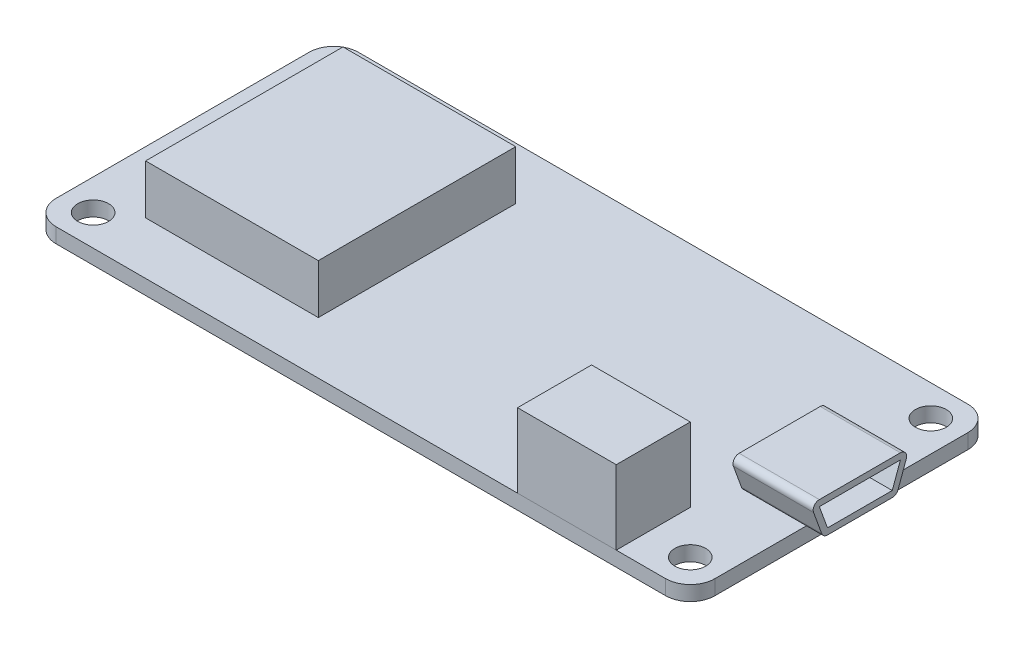
SolidWorks part; units mm, degrees
ref_plane "Front Plane" through (0, 0, 0) normal (0, 0, 1) x (1, 0, 0)
ref_plane "Top Plane" through (0, 0, 0) normal (0, 1, 0) x (1, 0, 0)
ref_plane "Right Plane" through (0, 0, 0) normal (1, 0, 0) x (0, 0, -1)
sketch "Sketch1" plane through (0, 0, 0) normal (0, 1, 0) x (1, 0, 0)
  line L1 (2, 0) -> (51.4, 0)
  line L2 (0, 2) -> (0, 22.5)
  line L3 (2, 24.5) -> (51.4, 24.5)
  line L4 (53.4, 2) -> (53.4, 22.5)
  line L5 (2.5, 22) -> (50.9, 22) construction
  line L6 (2.5, 22) -> (2.5, 2.5) construction
  line L7 (2.5, 2.5) -> (50.9, 2.5) construction
  line L8 (50.9, 22) -> (50.9, 2.5) construction
  arc A0 (51.4, 24.5) -> (53.4, 22.5) centre (51.4, 22.5) cw
  arc A1 (51.4, 0) -> (53.4, 2) centre (51.4, 2) ccw
  arc A2 (2, 0) -> (0, 2) centre (2, 2) cw
  arc A3 (0, 22.5) -> (2, 24.5) centre (2, 22.5) cw
  circle A4 centre (2.5, 22) radius 1.25
  circle A5 centre (50.9, 22) radius 1.25
  circle A6 centre (50.9, 2.5) radius 1.25
  circle A7 centre (2.5, 2.5) radius 1.25
  point P7 (53.4, 24.5)
  point P12 (0, 0)
  point P15 (0, 24.5)
  dimension "D2" = 2
  dimension "D3" = 2.5
  dimension "D1" = 24.5
  dimension "48.5" = 53.4
  dimension "D4" = 2.5
  dimension "D5" = 2.5
  dimension "D6" = 2.5
  dimension "D7" = 2.5
extrude "Boss-Extrude1" add sketch "Sketch1" along normal blind 1.2
sketch "Sketch2" plane through (53.4, 0, 0) normal (1, 0, 0) x (0, 0, -1)
  line L0 (2, 1.2) -> (22.5, 1.2) construction
  line L1 (8.9641, 4.0191) -> (15.5359, 4.0191)
  line L2 (8.4942, 3.3481) -> (9.1563, 1.529)
  line L3 (9.6262, 1.2) -> (14.8738, 1.2)
  line L4 (16.0058, 3.3481) -> (15.3437, 1.529)
  line L5 (8.9641, 3.5191) -> (9.6262, 1.7)
  line L6 (9.6262, 1.7) -> (14.8738, 1.7)
  line L7 (15.5359, 3.5191) -> (14.8738, 1.7)
  line L8 (8.9641, 3.5191) -> (15.5359, 3.5191)
  arc A0 (9.1563, 1.529) -> (9.6262, 1.2) centre (9.6262, 1.7) ccw
  arc A1 (14.8738, 1.2) -> (15.3437, 1.529) centre (14.8738, 1.7) ccw
  arc A2 (15.5359, 4.0191) -> (16.0058, 3.3481) centre (15.5359, 3.5191) cw
  arc A3 (8.9641, 4.0191) -> (8.4942, 3.3481) centre (8.9641, 3.5191) ccw
  arc A4 (8.9641, 3.5191) -> (8.9641, 3.5191) centre (8.9641, 3.5191) ccw
  arc A5 (9.6262, 1.7) -> (9.6262, 1.7) centre (9.6262, 1.7) ccw
  arc A6 (14.8738, 1.7) -> (14.8738, 1.7) centre (14.8738, 1.7) ccw
  arc A7 (15.5359, 3.5191) -> (15.5359, 3.5191) centre (15.5359, 3.5191) cw
  point P4 (12.25, 1.2)
  point P5 (12.25, 1.2)
  point P10 (9.2761, 1.2)
  point P15 (16.25, 4.0191)
  point P18 (8.25, 4.0191)
  dimension "D3" = 0.5
  dimension "D1" = 3
  dimension "D2" = 8
  dimension "D5" = 110
  dimension "D6" = 110
  dimension "D4" = 0.5
extrude "Boss-Extrude2" add sketch "Sketch2" against normal blind 5 and the other way blind 1.5 separate body
sketch "Sketch3" plane through (0, 1.2, 0) normal (0, 1, 0) x (1, 0, 0)
  line L1 (5, 20.25) -> (19, 20.25)
  line L2 (5, 20.25) -> (5, 4.25)
  line L3 (5, 4.25) -> (19, 4.25)
  line L4 (19, 20.25) -> (19, 4.25)
  line L7 (0, 22.5) -> (0, 2) construction
  line L8 (0, 12.25) -> (5, 12.25) construction
  dimension "D1" = 14
  dimension "D2" = 16
  dimension "D4" = 5
extrude "Boss-Extrude3" add sketch "Sketch3" along normal blind 4 separate body
sketch "Sketch4" plane through (0, 1.2, 0) normal (0, 1, 0) x (1, 0, 0)
  line L0 (2, 0) -> (51.4, 0) construction
  line L1 (47.4, 0) -> (39.4, 0)
  line L2 (47.4, 0) -> (47.4, 6)
  line L3 (47.4, 6) -> (39.4, 6)
  line L4 (39.4, 0) -> (39.4, 6)
  line L5 (53.4, 2) -> (53.4, 22.5) construction
  dimension "D1" = 6
  dimension "D2" = 8
  dimension "D3" = 6
extrude "Boss-Extrude4" add sketch "Sketch4" along normal blind 6 separate body
